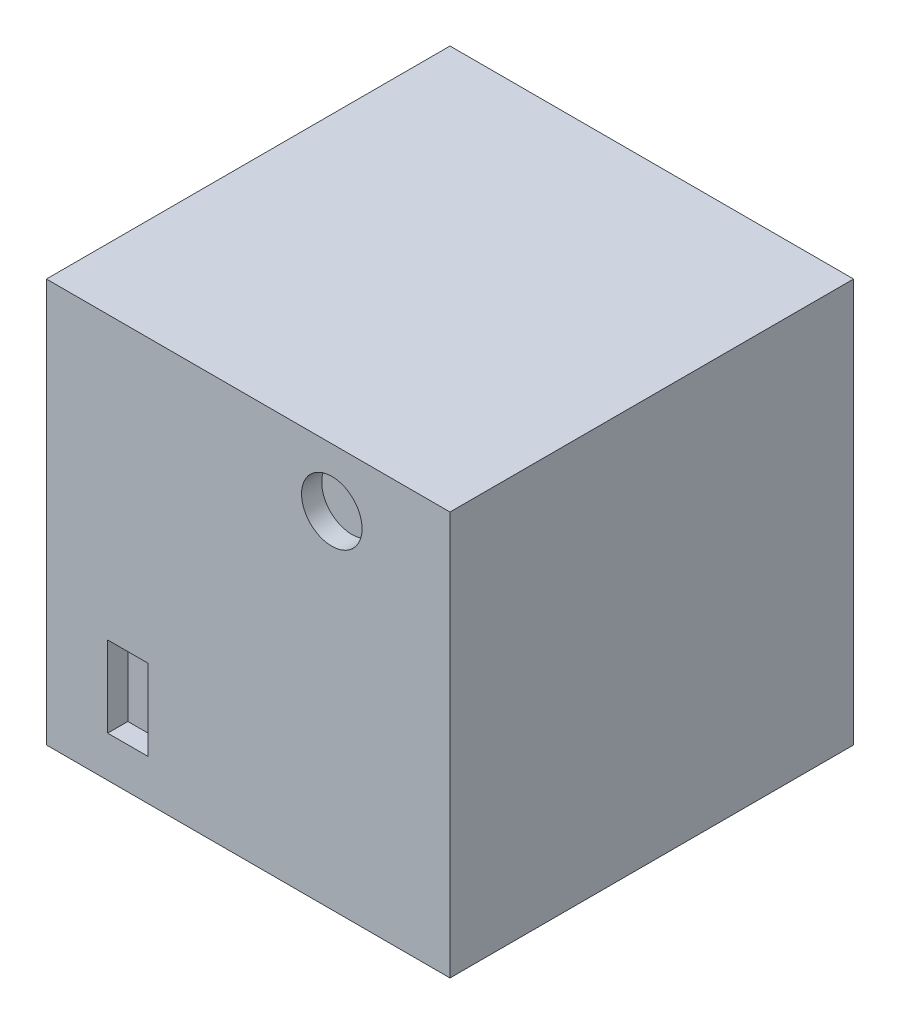
SolidWorks part; units mm, degrees
ref_plane "Front Plane" through (0, 0, 0) normal (0, 0, 1) x (1, 0, 0)
ref_plane "Top Plane" through (0, 0, 0) normal (0, 1, 0) x (1, 0, 0)
ref_plane "Right Plane" through (0, 0, 0) normal (1, 0, 0) x (0, 0, -1)
sketch "Sketch1" plane through (0, 0, 0) normal (0, 0, 1) x (1, 0, 0)
  line L1 (0, 0) -> (10, 0)
  line L2 (0, 0) -> (0, 10)
  line L3 (0, 10) -> (10, 10)
  line L4 (10, 0) -> (10, 10)
  line L5 (0, 0) -> (10, 10) construction
  line L6 (0, 10) -> (10, 0) construction
  point P4 (5, 5)
  dimension "D1" = 10
  dimension "D2" = 10
extrude "Boss-Extrude1" add sketch "Sketch1" against normal blind 10
ref_plane "Plane1" through (0, 0, -3) normal (0, 0, -1) x (-1, 0, 0)
sketch "Sketch3" plane through (0, 0, -3) normal (0, 0, -1) x (-1, 0, 0)
  circle A0 centre (-8.022, 7.6002) radius 1
  dimension "D1" = 2
extrude "Cut-Extrude1" cut sketch "Sketch3" against normal blind 1
sketch "Sketch4" plane through (0, 0, 0) normal (0, 0, 1) x (1, 0, 0)
  line L1 (1.5178, 3.0134) -> (2.5178, 3.0134)
  line L2 (1.5178, 3.0134) -> (1.5178, 1.0134)
  line L3 (1.5178, 1.0134) -> (2.5178, 1.0134)
  line L4 (2.5178, 3.0134) -> (2.5178, 1.0134)
  line L5 (1.5178, 3.0134) -> (2.5178, 1.0134) construction
  line L6 (1.5178, 1.0134) -> (2.5178, 3.0134) construction
  point P4 (2.0178, 2.0134)
  dimension "D1" = 1
  dimension "D2" = 2
extrude "Cut-Extrude2" cut sketch "Sketch4" against normal blind 0.5
sketch "Sketch5" plane through (0, 0, 0) normal (0, 0, 1) x (1, 0, 0)
  circle A0 centre (7.0709, 8.5513) radius 0.75
  dimension "D1" = 1.5
extrude "Cut-Extrude3" cut sketch "Sketch5" against normal blind 0.5
